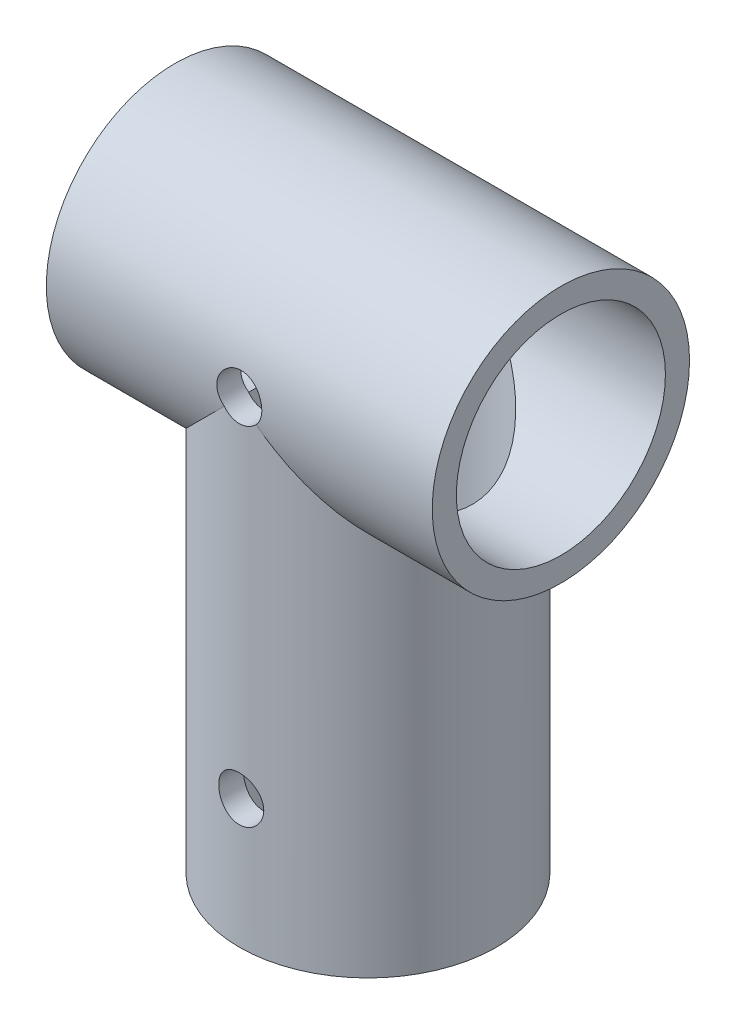
SolidWorks part; units mm, degrees
ref_plane "Front Plane" through (0, 0, 0) normal (0, 0, 1) x (1, 0, 0)
ref_plane "Top Plane" through (0, 0, 0) normal (0, 1, 0) x (1, 0, 0)
ref_plane "Right Plane" through (0, 0, 0) normal (1, 0, 0) x (0, 0, -1)
sketch "Sketch1" plane through (0, 0, 0) normal (0, 1, 0) x (1, 0, 0)
  circle A0 centre (0, 0) radius 8.125
  circle A1 centre (0, 0) radius 10
  dimension "D1" = 16.25
  dimension "D2" = 20
extrude "Boss-Extrude1" add sketch "Sketch1" along normal blind 25
sketch "Sketch2" plane through (0, 0, 0) normal (1, 0, 0) x (0, 0, -1)
  line L0 (0, 0) -> (0, 37) construction
  line L1 (10, 25) -> (-10, 25) construction
  circle A0 centre (0, 37) radius 8.125
  circle A1 centre (0, 37) radius 10
  dimension "D1" = 16.25
  dimension "D2" = 20
  dimension "D3" = 12
extrude "Boss-Extrude2" add sketch "Sketch2" along normal mid plane 30 separate body
sketch "Sketch4" plane through (0, 25, 0) normal (0, 1, 0) x (1, 0, 0)
  circle A0 centre (0, 0) radius 10
  dimension "D1" = 20
extrude "Boss-Extrude4" add sketch "Sketch4" along normal up to surface (12 mm away) up to face at (15, 37, -10)
sketch "Sketch7" plane through (0, 25, 0) normal (0, -1, 0) x (1, 0, 0)
  circle A0 centre (0, 0) radius 8.125
  dimension "D1" = 16.25
extrude "Cut-Extrude3" cut sketch "Sketch7" against normal up to surface (12 mm away) up to face at (15, 37, -8.125)
sketch "Sketch5" plane through (0, 0, 0) normal (0, 0, 1) x (1, 0, 0)
  line L0 (-10, 0) -> (10, 0) construction
  circle A0 centre (0, 10) radius 1.75
  dimension "D1" = 3.5
  dimension "D2" = 10
extrude "Cut-Extrude1" cut sketch "Sketch5" against normal through all both and the other way through all
sketch "Sketch6" plane through (0, 0, 0) normal (0, 0, 1) x (1, 0, 0)
  line L2 (15, 47) -> (-15, 47) construction
  circle A0 centre (0, 37) radius 1.75
  dimension "D2" = 3.5
  dimension "D1" = 10
extrude "Cut-Extrude2" cut sketch "Sketch6" against normal through all both and the other way through all
